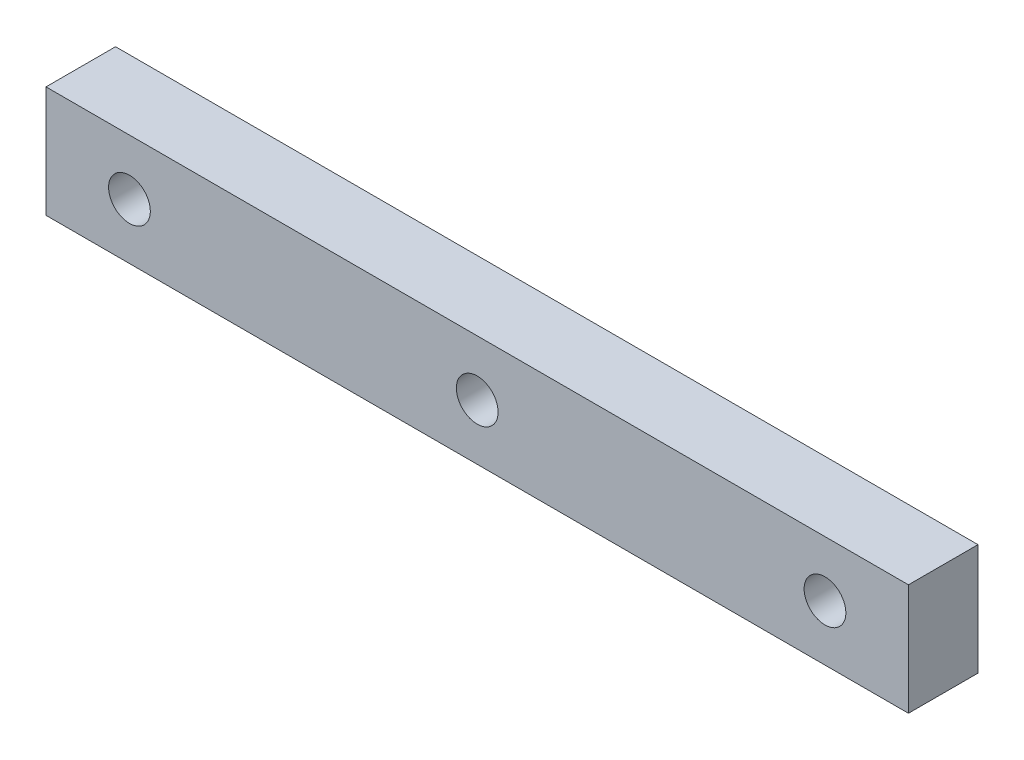
SolidWorks part; units mm, degrees
ref_plane "Front Plane" through (0, 0, 0) normal (0, 0, 1) x (1, 0, 0)
ref_plane "Top Plane" through (0, 0, 0) normal (0, 1, 0) x (1, 0, 0)
ref_plane "Right Plane" through (0, 0, 0) normal (1, 0, 0) x (0, 0, -1)
sketch "Sketch1" plane through (0, 0, 0) normal (0, 0, 1) x (1, 0, 0)
  line L1 (-31, 4) -> (31, 4)
  line L2 (-31, 4) -> (-31, -4)
  line L3 (-31, -4) -> (31, -4)
  line L4 (31, 4) -> (31, -4)
  dimension "D1" = 62
  dimension "D2" = 8
  dimension "D3" = 4
  dimension "D4" = 31
extrude "Boss-Extrude1" add sketch "Sketch1" along normal blind 5
sketch "Sketch2" plane through (0, 0, 0) normal (0, 0, -1) x (-1, 0, 0)
  circle A0 centre (-25, 0) radius 1.5
  circle A1 centre (0, 0) radius 1.5
  circle A2 centre (25, 0) radius 1.5
  dimension "D1" = 3
  dimension "D2" = 3
  dimension "D3" = 3
  dimension "D4" = 25
  dimension "D5" = 25
extrude "Cut-Extrude1" cut sketch "Sketch2" against normal blind 10
